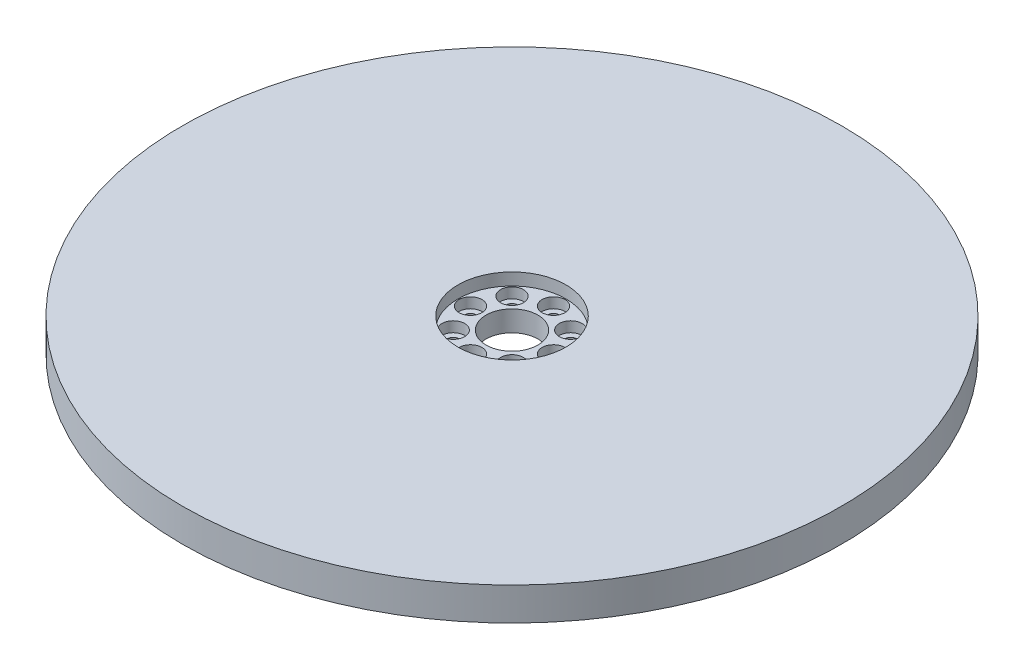
SolidWorks part; units mm, degrees
other "Markup1"
sketch "Sketch21" plane through (-65.5, -15.05, -60) normal (-0.0927, -0.2854, -0.9539) x (0.9951, -0.0609, -0.0785)
material "6061-T6 (SS)"
ref_plane "Front Plane" through (0, 0, 0) normal (0, 0, 1) x (1, 0, 0)
ref_plane "Top Plane" through (0, 0, 0) normal (0, 1, 0) x (1, 0, 0)
ref_plane "Right Plane" through (0, 0, 0) normal (1, 0, 0) x (0, 0, -1)
sketch "Sketch1" plane through (0, 0, 0) normal (0, 1, 0) x (1, 0, 0)
  circle A0 centre (0, 0) radius 63.5
  dimension "D1" = 127
extrude "Boss-Extrude1" add sketch "Sketch1" along normal blind 3.175
sketch "Sketch2" plane through (0, 0, 0) normal (0, -1, 0) x (1, 0, 0)
  circle A0 centre (0, 0) radius 12.9
  circle A1 centre (0, 0) radius 63.5 construction
  dimension "D1" = 25.8
extrude "Boss-Extrude2" add sketch "Sketch2" along normal blind 3.175
sketch "Sketch3" plane through (0, 0, 0) normal (0, -1, 0) x (1, 0, 0)
  circle A0 centre (0, 0) radius 25.4
  circle A1 centre (0, 0) radius 63.5
  circle A2 centre (0, 0) radius 12.9 construction
  dimension "D1" = 50.8
  dimension "D2" = 127
extrude "Boss-Extrude3" add sketch "Sketch3" along normal blind 3.175
sketch "Sketch5" plane through (0, 3.175, 0) normal (0, 1, 0) x (1, 0, 0)
  circle A0 centre (0, 0) radius 10.4
  circle A1 centre (0, 0) radius 63.5 construction
extrude "Cut-Extrude1" cut sketch "Sketch5" against normal offset from surface (2.35 mm away) 4 up to face at (0, -3.175, -12.9)
sketch "Sketch6" plane through (0, 0.825, 0) normal (0, 1, 0) x (1, 0, 0)
  circle A0 centre (0, 0) radius 5
  circle A1 centre (0, 0) radius 10.4 construction
extrude "Cut-Extrude2" cut sketch "Sketch6" along direction (0, -1, 0) on the side against the normal up to next (4 mm away)
sketch "Sketch15" plane through (0, -3.175, 0) normal (0, 1, 0) x (1, 0, 0)
  circle A0 centre (0, 8) radius 1
  circle A1 centre (-5.6569, 5.6569) radius 1
  circle A2 centre (5.6569, 5.6569) radius 1
  circle A3 centre (-5.6569, -5.6569) radius 1
  circle A4 centre (5.6569, -5.6569) radius 1
  circle A5 centre (-8, 0) radius 1
  circle A6 centre (0, -8) radius 1
  circle A7 centre (8, 0) radius 1
  circle A8 centre (0, 0) radius 4
  circle A9 centre (0, 0) radius 11
  circle A10 centre (0, 0) radius 2.25
  circle A11 centre (0, 0) radius 5
  circle A12 centre (0, 0) radius 5 construction
  dimension "D1" = 4.5
  dimension "D2" = 8
  dimension "D3" = 10
  dimension "D4" = 22
  dimension "D5" = 2
  dimension "D6" = 8
  dimension "D7" = 5.6569
  dimension "D8" = 8
  dimension "D9" = 5.6569
  dimension "D10" = 5.6569
  dimension "D11" = 8
  dimension "D12" = 5.6569
  dimension "D13" = 8
hole_wizard "CBORE for M2 SHCS1" positions "Sketch19" profile "Sketch20" counterbore size "M2" standard "ANSI Metric"
sketch "Sketch19" plane through (0, 0.825, 0) normal (0, 1, 0) x (1, 0, 0)
  point P0 (-5.6569, 5.6569)
  point P3 (0, 8)
  point P6 (5.6569, 5.6569)
  point P9 (8, 0)
  point P12 (5.6569, -5.6569)
  point P15 (0, -8)
  point P18 (-5.6569, -5.6569)
  point P21 (-8, 0)
sketch "Sketch20" plane through (-5.6569, 0.825, -5.6569) normal (1, 0, 0) x (0, 0, 1)
  line L0 (0, 0) -> (0, 6.6609)
  line L1 (0, 6.6609) -> (1.1, 6)
  line L2 (1.1, 6) -> (1.1, 2)
  line L3 (1.1, 2) -> (2.2, 2)
  line L4 (2.2, 2) -> (2.2, 0)
  line L5 (2.2, 0) -> (0, 0)
  line L10 (0, 6.6609) -> (-1.1, 6) construction
  line L11 (0, -6.35) -> (0, 107.95) construction
  dimension "Hole Dia." = 2.2
  dimension "Hole Depth" = 6
  dimension "C'Bore Dia." = 4.4
  dimension "C'Bore Depth" = 2
  dimension "Drill Angle" = 118
sketch "Sketch22" [suppressed] plane through (0, -3.175, 0) normal (0, -1, 0) x (1, 0, 0)
  line L0 (-5, 53.768) -> (-5, 33.6303)
  line L4 (5, 53.768) -> (5, 33.6303)
  line L9 (-65.5, 25) -> (-65.5, -25) construction
  line L10 (34.4842, 41.5553) -> (20.2447, 27.3158)
  line L11 (41.5553, 34.4842) -> (27.3158, 20.2447)
  line L12 (53.768, 5) -> (33.6303, 5)
  line L13 (53.768, -5) -> (33.6303, -5)
  line L14 (41.5553, -34.4842) -> (27.3158, -20.2447)
  line L15 (34.4842, -41.5553) -> (20.2447, -27.3158)
  line L16 (5, -53.768) -> (5, -33.6303)
  line L17 (-5, -53.768) -> (-5, -33.6303)
  line L18 (-34.4842, -41.5553) -> (-20.2447, -27.3158)
  line L19 (-41.5553, -34.4842) -> (-27.3158, -20.2447)
  line L20 (-53.768, -5) -> (-33.6303, -5)
  line L21 (-53.768, 5) -> (-33.6303, 5)
  line L22 (-41.5553, 34.4842) -> (-27.3158, 20.2447)
  line L23 (-34.4842, 41.5553) -> (-20.2447, 27.3158)
  line L24 (-54.5436, 25) -> (-65.5, 25) construction
  arc A0 (-5, 53.768) -> (-34.4842, 41.5553) centre (0, 0) ccw
  arc A1 (-5, 33.6303) -> (-20.2447, 27.3158) centre (0, 0) ccw
  arc A2 (-41.5553, 34.4842) -> (-53.768, 5) centre (0, 0) ccw
  arc A3 (-27.3158, 20.2447) -> (-33.6303, 5) centre (0, 0) ccw
  arc A4 (-33.6303, -5) -> (-27.3158, -20.2447) centre (0, 0) ccw
  arc A5 (-53.768, -5) -> (-41.5553, -34.4842) centre (0, 0) ccw
  arc A6 (-34.4842, -41.5553) -> (-5, -53.768) centre (0, 0) ccw
  arc A7 (-20.2447, -27.3158) -> (-5, -33.6303) centre (0, 0) ccw
  arc A8 (5, -53.768) -> (34.4842, -41.5553) centre (0, 0) ccw
  arc A9 (5, -33.6303) -> (20.2447, -27.3158) centre (0, 0) ccw
  arc A10 (27.3158, -20.2447) -> (33.6303, -5) centre (0, 0) ccw
  arc A11 (41.5553, -34.4842) -> (53.768, -5) centre (0, 0) ccw
  arc A12 (33.6303, 5) -> (27.3158, 20.2447) centre (0, 0) ccw
  arc A13 (53.768, 5) -> (41.5553, 34.4842) centre (0, 0) ccw
  arc A14 (20.2447, 27.3158) -> (5, 33.6303) centre (0, 0) ccw
  arc A15 (34.4842, 41.5553) -> (5, 53.768) centre (0, 0) ccw
  point P36 (0, 0)
  dimension "D1" = 8
  dimension "D2" = 54
  dimension "D3" = 34
  dimension "D4" = 119.268
  dimension "D5" = 11.732
  dimension "D6" = 6.3146
  dimension "D7" = 2.3158
